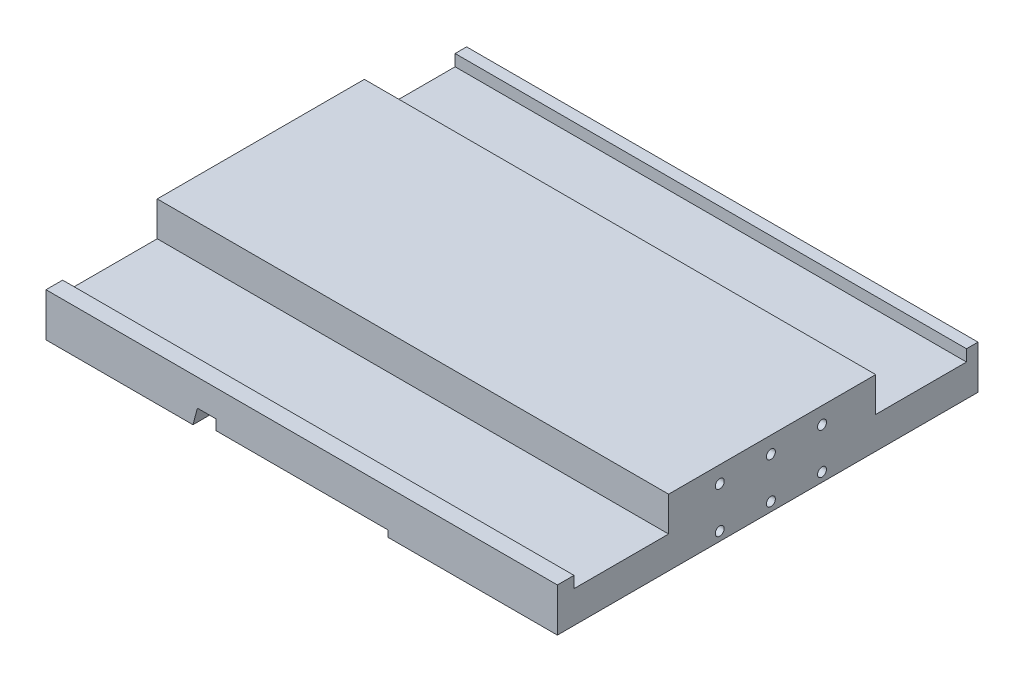
SolidWorks part; units mm, degrees
ref_plane "前视基准面" through (0, 0, 0) normal (0, 0, 1) x (1, 0, 0)
ref_plane "上视基准面" through (0, 0, 0) normal (0, 1, 0) x (1, 0, 0)
ref_plane "右视基准面" through (0, 0, 0) normal (1, 0, 0) x (0, 0, -1)
other "Configuration Table"
sketch "草图1" plane through (0, 0, 0) normal (0, 1, 0) x (1, 0, 0)
  line L1 (0, 0) -> (400, 0)
  line L2 (0, 0) -> (0, 329)
  line L3 (0, 329) -> (400, 329)
  line L4 (400, 0) -> (400, 329)
extrude "凸台-拉伸1" add sketch "草图1" along normal blind 25
sketch "草图2" plane through (0, 25, 0) normal (0, 1, 0) x (1, 0, 0)
  line L1 (0, 329) -> (0, 0) construction
  line L2 (0, 249) -> (400, 249)
  line L3 (400, 0) -> (400, 329) construction
  line L4 (400, 249) -> (400, 87)
  line L5 (400, 87) -> (0, 87)
  line L6 (0, 87) -> (0, 249)
extrude "凸台-拉伸2" add sketch "草图2" along normal blind 27
sketch "草图3" plane through (0, 25, 0) normal (0, 1, 0) x (1, 0, 0)
  line L6 (0, 0) -> (0, 21.5)
  line L7 (0, 87) -> (0, 0) construction
  circle A0 centre (27.5, 312.5) radius 4.5
  circle A1 centre (72.5, 312.5) radius 4.5
  circle A2 centre (27.5, 255.5) radius 4.5
  circle A3 centre (72.5, 255.5) radius 4.5
  circle A4 centre (27.5, 78.5) radius 4.5
  circle A5 centre (72.5, 78.5) radius 4.5
  circle A6 centre (72.5, 21.5) radius 4.5
  circle A7 centre (27.5, 21.5) radius 4.5
  circle A8 centre (372.5, 21.5) radius 4.5
  circle A9 centre (327.5, 21.5) radius 4.5
  circle A10 centre (327.5, 78.5) radius 4.5
  circle A11 centre (372.5, 78.5) radius 4.5
  circle A12 centre (327.5, 255.5) radius 4.5
  circle A13 centre (372.5, 255.5) radius 4.5
  circle A14 centre (327.5, 312.5) radius 4.5
  circle A15 centre (372.5, 312.5) radius 4.5
extrude "切除-拉伸1" [suppressed] cut sketch "草图3" against normal blind 27 contours A0 | A1 | A3 | A2 | A4 | A5 | A7 | A6 | A14 | A15 | A12 | A13 | A10 | A11 | A9 | A8
sketch "草图4" plane through (0, 25, 0) normal (0, 1, 0) x (1, 0, 0)
  line L0 (0, 329) -> (0, 320)
  line L1 (0, 329) -> (0, 249) construction
  line L2 (0, 320) -> (400, 320)
  line L3 (400, 249) -> (400, 329) construction
  line L4 (400, 320) -> (400, 329)
  line L5 (400, 329) -> (0, 329)
  line L6 (0, 0) -> (0, 13)
  line L7 (0, 87) -> (0, 0) construction
  line L8 (0, 13) -> (400, 13)
  line L9 (400, 0) -> (400, 87) construction
  line L10 (400, 13) -> (400, 0)
  line L11 (400, 0) -> (0, 0)
extrude "凸台-拉伸3" add sketch "草图4" along normal blind 9
sketch "草图7" [suppressed] plane through (0, 0, 0) normal (0, -1, 0) x (1, 0, 0)
  circle A0 centre (27.5, -21.5) radius 7
  circle A1 centre (27.5, -78.5) radius 7
  circle A2 centre (72.5, -78.5) radius 7
  circle A3 centre (72.5, -21.5) radius 7
  circle A4 centre (327.5, -21.5) radius 7
  circle A5 centre (372.5, -21.5) radius 7
  circle A6 centre (327.5, -78.5) radius 7
  circle A7 centre (372.5, -78.5) radius 7
extrude "切除-拉伸2" [suppressed] cut sketch "草图7" against normal blind 10
sketch "草图8" plane through (0, 0, -329) normal (0, 0, -1) x (-1, 0, 0)
  line L0 (-400, 0) -> (-267.5, 0)
  line L1 (-400, 0) -> (0, 0) construction
  line L2 (-267.5, 0) -> (-267.5, 5)
  line L3 (-267.5, 5) -> (-133, 5)
  line L4 (-133, 5) -> (-133, 13.0669)
  line L5 (-133, 13.0669) -> (-118.4594, 13.0669)
  line L6 (-118.4594, 13.0669) -> (-114.9581, 0)
  line L7 (-114.9581, 0) -> (-267.5, 0)
  line M4 (-400, 0) -> (0, 0)
extrude "切除-拉伸3" cut sketch "草图8" against normal blind 400 contours L6 L5 L4 L3 L2 M4
sketch "草图9" plane through (0, 5, 0) normal (0, -1, 0) x (1, 0, 0)
  line L5 (140, -67) -> (140, -114) construction
  circle A0 centre (260, -67) radius 3.5
  circle A1 centre (140, -67) radius 3.5
  circle A2 centre (140, -114) radius 3.5
  circle A3 centre (260, -114) radius 3.5
  circle A4 centre (140, -161) radius 3.5
  circle A5 centre (260, -161) radius 3.5
  circle A6 centre (140, -208) radius 3.5
  circle A7 centre (260, -208) radius 3.5
  dimension "D1" = 4
  dimension "D2" = 47
extrude "切除-拉伸4" [suppressed] cut sketch "草图9" against normal blind 24
sketch "草图10" plane through (0, 13.0669, 0) normal (0, -1, 0) x (1, 0, 0)
  circle A0 centre (124.5, -37) radius 2
  circle A1 centre (124.5, -63) radius 2
  circle A2 centre (124.5, -89) radius 2
  circle A3 centre (124.5, -115) radius 2
  circle A4 centre (124.5, -141) radius 2
  circle A5 centre (124.5, -167) radius 2
  circle A6 centre (124.5, -193) radius 2
  circle A7 centre (124.5, -219) radius 2
  circle A8 centre (124.5, -245) radius 2
  dimension "D1" = 9
extrude "切除-拉伸8" cut sketch "草图10" against normal blind 9.03
sketch "草图12" plane through (0, 13.0669, 0) normal (0, -1, 0) x (1, 0, 0)
  line L1 (118.4594, 0) -> (133, 0)
  line L2 (118.4594, 0) -> (118.4594, -329)
  line L3 (118.4594, -329) -> (133, -329)
  line L4 (133, 0) -> (133, -329)
  circle A0 centre (124.5, -37) radius 2
  circle A1 centre (124.5, -63) radius 2
  circle A2 centre (124.5, -89) radius 2
  circle A3 centre (124.5, -89) radius 2
  circle A4 centre (124.5, -115) radius 2
  circle A5 centre (124.5, -141) radius 2
  circle A6 centre (124.5, -167) radius 2
  circle A7 centre (124.5, -193) radius 2
  circle A8 centre (124.5, -219) radius 2
  circle A9 centre (124.5, -245) radius 2
  circle M5 centre (124.5, -37) radius 2
  circle M6 centre (124.5, -63) radius 2
  circle M7 centre (124.5, -89) radius 2
  circle M8 centre (124.5, -115) radius 2
  circle M9 centre (124.5, -141) radius 2
  circle M10 centre (124.5, -167) radius 2
  circle M11 centre (124.5, -193) radius 2
  circle M12 centre (124.5, -219) radius 2
  circle M13 centre (124.5, -245) radius 2
  line M14 (133, 0) -> (118.4594, 0)
  line M15 (118.4594, 0) -> (118.4594, -329)
  line M16 (118.4594, -329) -> (133, -329)
  line M17 (133, -329) -> (133, 0)
extrude "凸台-拉伸4" add sketch "草图12" along normal blind 0.07 contours M17 M14 M15 M16 M6 M8 M10 M12 M13 M11 M9 M7 M5
sketch "草图13" plane through (0, 0, 0) normal (0, 0, 1) x (1, 0, 0)
  line L0 (118.4594, 13.0669) -> (118.4594, 12.9969)
  line L1 (118.4594, 12.9969) -> (118.4406, 12.9969)
  line L2 (118.4594, 13.0669) -> (114.9581, 0) construction
  line L3 (118.4406, 12.9969) -> (118.4594, 13.0669)
extrude "凸台-拉伸5" add sketch "草图13" against normal blind 329
sketch "草图15" plane through (400, 0, 0) normal (1, 0, 0) x (0, 0, -1)
  line L0 (249, 52) -> (207, 52)
  line L1 (87, 52) -> (249, 52) construction
  line L2 (207, 52) -> (207, 39.0268)
  line L3 (207, 39.0268) -> (167, 39.0268)
  line L4 (167, 39.0268) -> (167, 7.0268)
  line L5 (167, 7.0268) -> (127, 7.0268)
  line L6 (127, 7.0268) -> (127, 39.0268)
  line L7 (167, 7.0268) -> (207, 7.0268)
  circle A0 centre (207, 39.0268) radius 3.5
  circle A1 centre (207, 7.0268) radius 3.5
  circle A2 centre (167, 39.0268) radius 3.5
  circle A3 centre (167, 7.0268) radius 3.5
  circle A4 centre (127, 39.0268) radius 3.5
  circle A5 centre (127, 7.0268) radius 3.5
extrude "切除-拉伸10" cut sketch "草图15" against normal blind 22 contours A0 | A1 | A2 | A3 | A4 | A5
